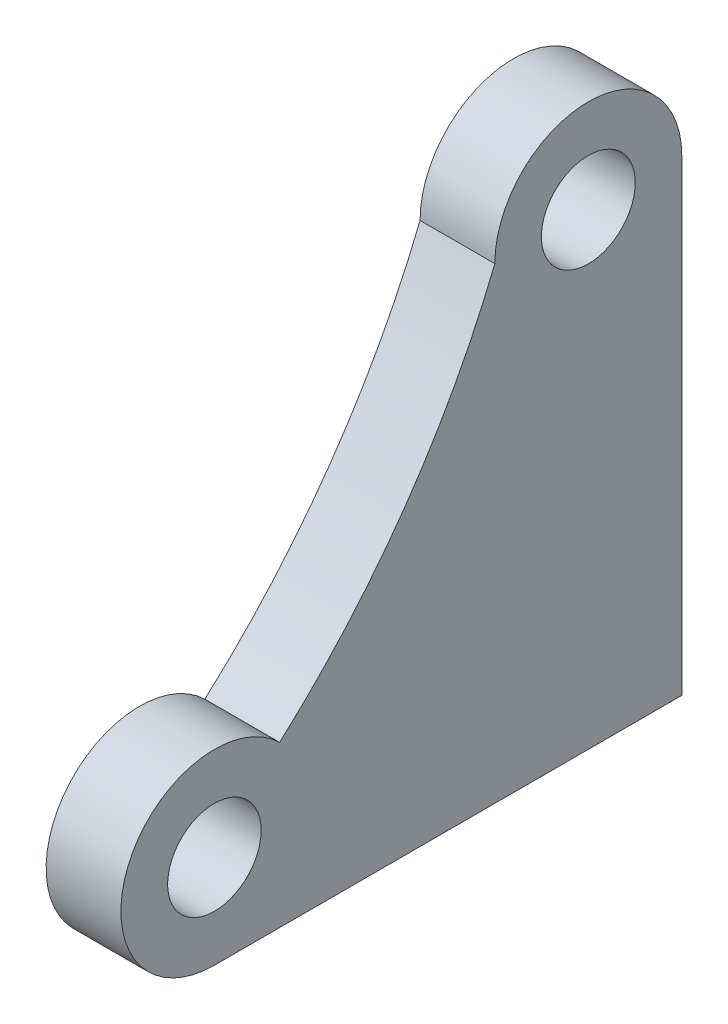
SolidWorks part; units mm, degrees
ref_plane "Alzado" through (0, 0, 0) normal (0, 0, 1) x (1, 0, 0)
ref_plane "Planta" through (0, 0, 0) normal (0, 1, 0) x (1, 0, 0)
ref_plane "Vista lateral" through (0, 0, 0) normal (1, 0, 0) x (0, 0, -1)
sketch "Croquis3" plane through (0, 0, 0) normal (1, 0, 0) x (0, 0, -1)
  line L0 (-20, -20) -> (0, -20) construction
  line L1 (0, -20) -> (0, 0) construction
  line L3 (5, 0) -> (5, -35) construction
  line L4 (5, 0) -> (5, -25)
  line L6 (5, -25) -> (-20, -25)
  line L8 (0, 0) -> (-20, -20) construction
  circle A0 centre (0, 0) radius 2.5103
  arc A1 (-16.5109, -16.4186) -> (-5, 0) centre (-46.0992, 16.5698) ccw
  circle A5 centre (-20, -20) radius 2.5
  arc A8 (-16.5109, -16.4186) -> (-20, -25) centre (-20, -20) ccw
  arc A9 (5, 0) -> (-5, 0) centre (0, 0) ccw
  dimension "D1" = 20
  dimension "D5" = 5
  dimension "D2" = 5.0207
  dimension "D3" = 20
  dimension "D4" = 5
extrude "Saliente-Extruir1" add sketch "Croquis3" along normal blind 4
